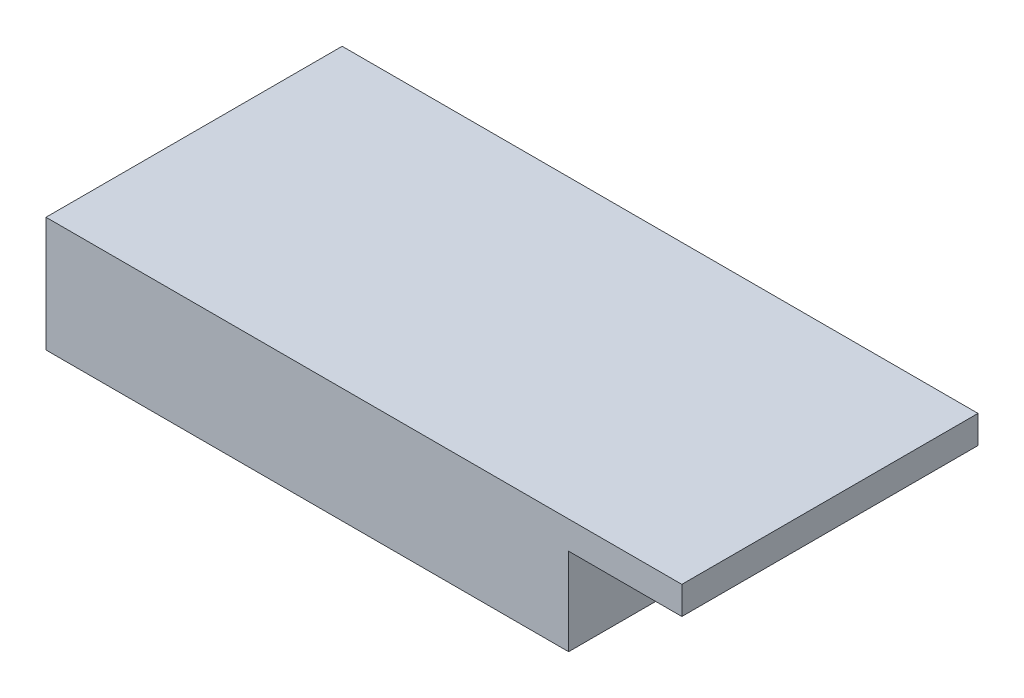
SolidWorks part; units mm, degrees
ref_plane "Front Plane" through (0, 0, 0) normal (0, 0, 1) x (1, 0, 0)
ref_plane "Top Plane" through (0, 0, 0) normal (0, 1, 0) x (1, 0, 0)
ref_plane "Right Plane" through (0, 0, 0) normal (1, 0, 0) x (0, 0, -1)
sketch "Sketch1" plane through (0, 0, 0) normal (0, 1, 0) x (1, 0, 0)
  line L1 (0, 0) -> (30, 0)
  line L2 (0, 0) -> (0, 17)
  line L3 (0, 17) -> (30, 17)
  line L4 (30, 0) -> (30, 17)
  dimension "D1" = 30
  dimension "D2" = 17
extrude "Boss-Extrude1" add sketch "Sketch1" along normal blind 6.6
sketch "Sketch2" plane through (0, 6.6, 0) normal (0, 1, 0) x (1, 0, 0)
  line L1 (30, 17) -> (36.5, 17)
  line L2 (30, 17) -> (30, 0)
  line L3 (30, 0) -> (36.5, 0)
  line L4 (36.5, 17) -> (36.5, 0)
  point P4 (0, 0)
  dimension "D1" = 6.5
extrude "Boss-Extrude2" add sketch "Sketch2" against normal blind 1.6
